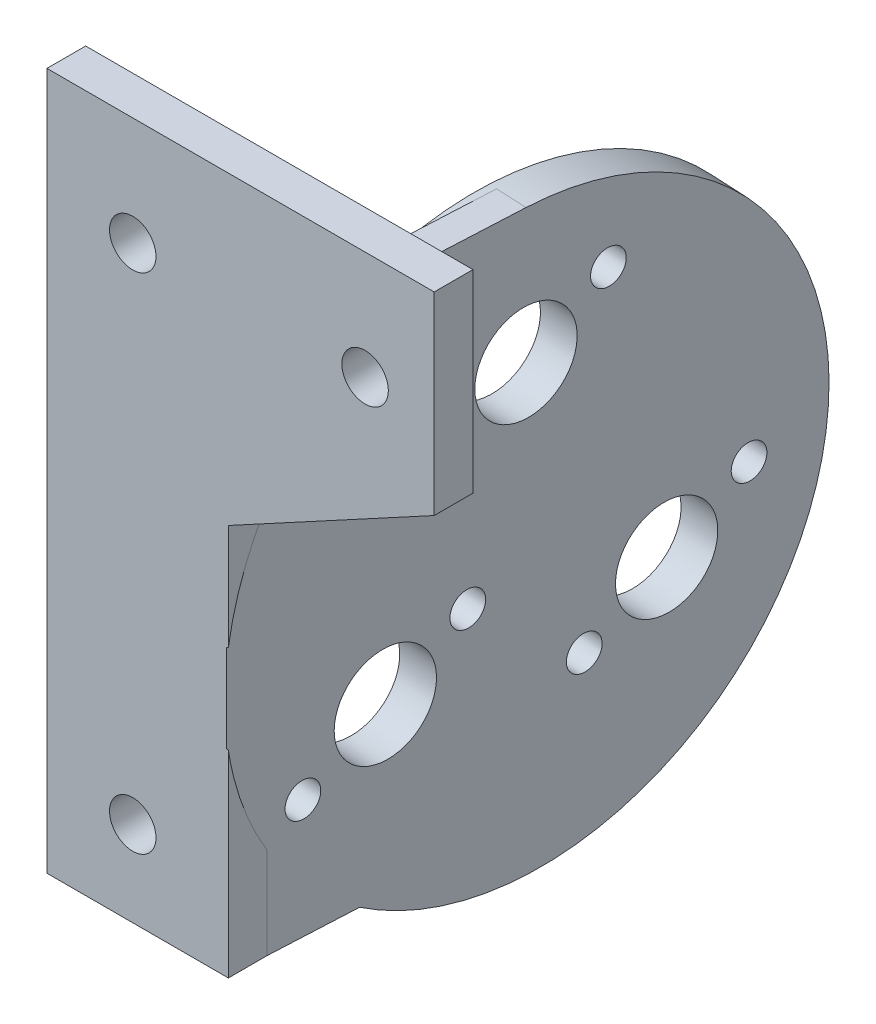
SolidWorks part; units mm, degrees
ref_plane "Front Plane" through (0, 0, 0) normal (0, 0, 1) x (1, 0, 0)
ref_plane "Top Plane" through (0, 0, 0) normal (0, 1, 0) x (1, 0, 0)
ref_plane "Right Plane" through (0, 0, 0) normal (1, 0, 0) x (0, 0, -1)
sketch "Sketch1" plane through (250.9675, 0, 12.4939) normal (-0.9988, 0, -0.0497) x (-0.0497, 0, 0.9988)
  line L4 (-63.8852, 38.4285) -> (-63.8852, -18.4675)
  line L5 (-56.9134, 38.4285) -> (-63.8852, 38.4285)
  line L6 (-56.9134, -21.6425) -> (-56.9134, 38.4285)
  line L7 (-62.6223, -21.6425) -> (-56.9134, -21.6425)
  line L8 (-63.8852, 38.4285) -> (-63.8852, -18.4675)
  line L9 (-56.9134, 38.4285) -> (-63.8852, 38.4285)
  line L10 (-56.9134, -21.6425) -> (-56.9134, 38.4285)
  line L11 (-62.6223, -21.6425) -> (-56.9134, -21.6425)
  line L12 (-63.8852, 38.4285) -> (-63.8852, -18.4675)
  line L13 (-56.9134, 38.4285) -> (-63.8852, 38.4285)
  line L14 (-56.9134, -21.6425) -> (-56.9134, 38.4285)
  line L15 (-62.6223, -21.6425) -> (-56.9134, -21.6425)
  line L16 (-63.8852, 38.4285) -> (-63.8852, -18.4675)
  line L17 (-56.9134, 38.4285) -> (-63.8852, 38.4285)
  line L18 (-56.9134, -21.6425) -> (-56.9134, 38.4285)
  line L19 (-62.6223, -21.6425) -> (-56.9134, -21.6425)
  line L58 (-62.6223, -18.4675) -> (-62.6223, -21.6425)
  line L59 (-62.6223, -18.4675) -> (-62.6223, -21.6425)
  line L60 (-63.8852, -18.4675) -> (-62.6223, -18.4675)
  line L61 (-63.8852, -18.4675) -> (-62.6223, -18.4675)
  line L62 (-62.6223, -18.4675) -> (-62.6223, -21.6425)
  line L63 (-62.6223, -18.4675) -> (-62.6223, -21.6425)
  line L64 (-63.8852, -18.4675) -> (-62.6223, -18.4675)
  line L65 (-63.8852, -18.4675) -> (-62.6223, -18.4675)
  circle A0 centre (-10.7836, -1.5384) radius 1.397 construction
  circle A1 centre (-10.7836, -1.5384) radius 1.397
  circle A2 centre (2.1066, -8.9806) radius 1.397 construction
  circle A3 centre (13.1052, 10.0694) radius 1.397 construction
  circle A4 centre (0.2149, 17.5116) radius 1.397 construction
  circle A5 centre (11.2134, -1.5384) radius 1.397 construction
  circle A6 centre (24.1037, -8.9806) radius 1.397 construction
  circle A7 centre (2.1066, -8.9806) radius 1.397
  circle A8 centre (13.1052, 10.0694) radius 1.397
  circle A9 centre (0.2149, 17.5116) radius 1.397
  circle A10 centre (11.2134, -1.5384) radius 1.397
  circle A11 centre (24.1037, -8.9806) radius 1.397
  circle A12 centre (6.66, 1.0905) radius 23.6982
  arc A13 (-0.6425, 22.0145) -> (13.9625, 22.0145) centre (6.66, 13.7905) ccw construction
  arc A14 (24.9611, -13.4834) -> (10.3561, -13.4834) centre (17.6586, -5.2595) ccw construction
  arc A15 (2.964, -13.4834) -> (-11.641, -13.4834) centre (-4.3385, -5.2595) ccw construction
  circle A16 centre (6.66, 13.7905) radius 4.0005
  circle A17 centre (-4.3385, -5.2595) radius 4.0005
  circle A18 centre (17.6586, -5.2595) radius 4.0005
  arc M9 (-0.6425, 22.0145) -> (13.9625, 22.0145) centre (6.66, 13.7905) ccw
  line M10 (13.9625, 22.0145) -> (13.9625, 26.6175)
  line M12 (-0.6425, 26.6175) -> (-0.6425, 22.0145)
  circle M13 centre (0.2149, 17.5116) radius 1.397
  circle M14 centre (13.1052, 10.0694) radius 1.397
  dimension "D3" = 8.001
  dimension "D1" = 0
  dimension "D2" = 0
extrude "Boss-Extrude1" add sketch "Sketch1" along normal blind 3.175 contours A12 A18 A17 A1 A7 A10 A11 M12 M10 M9 | A12 A16 M10 M12 M9 M13 M14
sketch "Sketch2" plane through (0, 0, 42.5406) normal (0, 0, -1) x (-1, 0, 0)
  line L1 (-266.5059, -18.7215) -> (-234.7559, -18.7215)
  line L2 (-266.5059, -18.7215) -> (-266.5059, 38.4285)
  line L3 (-266.5059, 38.4285) -> (-234.7559, 38.4285)
  line L4 (-234.7559, -18.7215) -> (-234.7559, 38.4285)
  line L5 (-301.4309, 38.4285) -> (-162.3949, 38.4285) construction
  dimension "D1" = 31.75
  dimension "D2" = 34.925
  dimension "D3" = 57.15
extrude "Boss-Extrude2" add sketch "Sketch2" along normal blind 3.175
sketch "Sketch3" plane through (0, 0, 39.3656) normal (0, 0, -1) x (-1, 0, 0)
  line L0 (-249.6297, 13.4091) -> (-266.5059, 22.5535)
  line L1 (-266.5059, 38.4285) -> (-266.5059, -18.7215) construction
  line L2 (-266.5059, 22.5535) -> (-266.5059, -18.7215)
  line L3 (-266.5059, -18.7215) -> (-249.6297, -18.7215)
  line L4 (-249.6297, -18.7215) -> (-249.6297, 13.4091)
  line L5 (-266.5059, -18.7215) -> (-234.7559, -18.7215) construction
  line L6 (-234.7559, 38.4285) -> (-266.5059, 38.4285) construction
  dimension "D1" = 15.875
extrude "Cut-Extrude2" cut sketch "Sketch3" against normal blind 3.175
sketch "Sketch4" plane through (250.9675, 0, 12.4939) normal (0.9988, 0, 0.0497) x (0.0497, 0, -0.9988)
  circle A0 centre (-6.66, 1.0905) radius 23.6982
extrude "Cut-Extrude3" cut sketch "Sketch4" along normal blind 2.54
sketch "Sketch5" plane through (0, 0, 42.5406) normal (0, 0, 1) x (1, 0, 0)
  line L0 (249.6297, -18.7215) -> (249.6297, 13.4091)
  line L1 (249.6297, 13.4091) -> (234.7559, 13.4091)
  line L2 (234.7559, -18.7215) -> (234.7559, 38.4285) construction
  line L3 (234.7559, 13.4091) -> (234.7559, -18.7215)
  line L4 (234.7559, -18.7215) -> (249.6297, -18.7215)
extrude "Cut-Extrude4" cut sketch "Sketch5" along normal blind 2.54
sketch "Sketch6" plane through (250.9675, 0, 12.4939) normal (0.9988, 0, 0.0497) x (0.0497, 0, -0.9988)
  line L0 (-30.0761, -18.7215) -> (-30.0761, -2.5555) construction
  line L1 (-30.0761, -18.7215) -> (-30.0761, -2.5555)
  line L2 (-30.0761, -18.7215) -> (-19.6635, -18.7215)
  line L3 (-30.0761, 4.7366) -> (-30.0761, 13.4091) construction
  line L4 (-30.0761, 4.7366) -> (-30.0761, 13.4091)
  line L5 (-6.66, 24.7887) -> (-30.0761, 24.7887)
  line L6 (-30.0761, 24.7887) -> (-30.0761, 13.4091)
  arc A0 (-26.905, -11.228) -> (-26.905, 13.4091) centre (-6.66, 1.0905) ccw construction
  circle A1 centre (-6.66, 1.0905) radius 23.6982
  arc M13 (-30.0839, -2.5047) -> (-26.905, -11.228) centre (-6.66, 1.0905) ccw
  arc M14 (-26.905, -11.228) -> (-26.905, 13.4091) centre (-6.66, 1.0905) ccw
  arc M15 (-26.905, 13.4091) -> (-30.0839, 4.6858) centre (-6.66, 1.0905) ccw
extrude "Boss-Extrude3" add sketch "Sketch6" against normal blind 2.54 contours L5 L6 L4 M15 M14 | L1 L2 M14 M13
sketch "Sketch9" plane through (0, 0, 42.5406) normal (0, 0, 1) x (1, 0, 0)
  circle A0 centre (260.8397, 29.5385) radius 1.905
  circle A1 centre (241.7897, 29.5385) radius 1.905
  circle A2 centre (241.7897, -11.7365) radius 1.905
  dimension "D1" = 3.81
extrude "Cut-Extrude6" cut sketch "Sketch9" against normal blind 6.35
